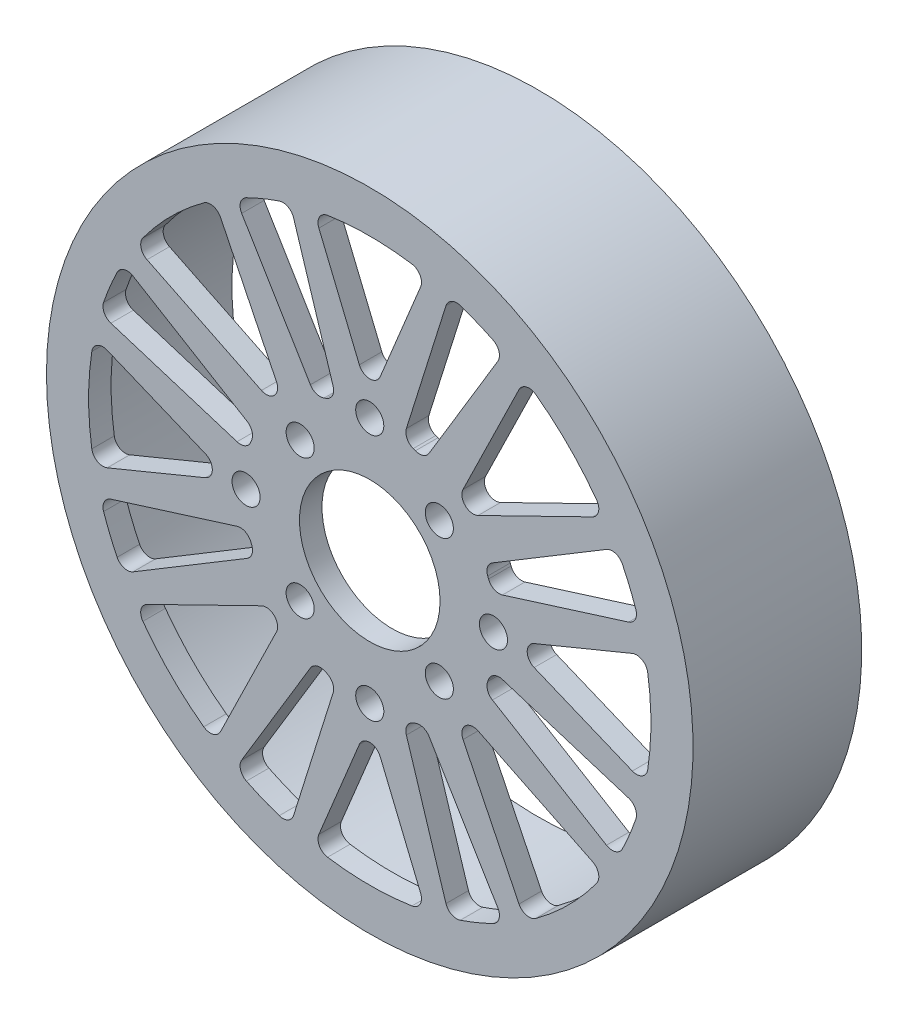
SolidWorks part; units mm, degrees
material "6061 合金"
ref_plane "前视基准面" through (0, 0, 0) normal (0, 0, 1) x (1, 0, 0)
ref_plane "上视基准面" through (0, 0, 0) normal (0, 1, 0) x (1, 0, 0)
ref_plane "右视基准面" through (0, 0, 0) normal (1, 0, 0) x (0, 0, -1)
sketch "草图1" plane through (0, 0, 0) normal (0, 0, 1) x (1, 0, 0)
  circle A0 centre (0, 0) radius 67.5
  dimension "D1" = 135
extrude "凸台-拉伸1" add sketch "草图1" along normal blind 4
sketch "草图2" plane through (0, 0, 4) normal (0, 0, 1) x (1, 0, 0)
  line L0 (0, 17.5) -> (0, 0) construction
  line L1 (0, 0) -> (12.3744, 12.3744) construction
  circle A0 centre (0, 0) radius 22 construction
  circle A1 centre (0, 0) radius 17.5 construction
  circle A2 centre (0, 22) radius 2.5
  circle A3 centre (12.3744, 12.3744) radius 2.5
  dimension "D1" = 35
  dimension "D2" = 44
  dimension "D4" = 5
  dimension "D3" = 45
extrude "切除-拉伸1" cut sketch "草图2" against normal through all
pattern_circular "阵列(圆周)1" count 4 over 360 about axis through (0, 0, 0) along (0, 0, 1) of "切除-拉伸1"
sketch "草图3" plane through (0, 0, 4) normal (0, 0, 1) x (1, 0, 0)
  circle A0 centre (0, 0) radius 12.5
  dimension "D1" = 25
extrude "切除-拉伸2" cut sketch "草图3" against normal through all
sketch "草图4" plane through (0, 0, 0) normal (0, 0, -1) x (-1, 0, 0)
  circle A0 centre (0, 0) radius 67.5
  circle A1 centre (0, 0) radius 54.5
  circle A2 centre (0, 0) radius 67.5 construction
  dimension "D1" = 13
extrude "凸台-拉伸2" add sketch "草图4" along normal offset from surface (26 mm away) 30 up to face at (12.5, 0, 4)
sketch "草图5" plane through (0, 0, -26) normal (0, 0, -1) x (-1, 0, 0)
  circle A0 centre (0, 0) radius 67.5
  circle A1 centre (0, 0) radius 57.5
  dimension "D1" = 10
extrude "切除-拉伸3" cut sketch "草图5" against normal through all
sketch "草图6" plane through (0, 0, 4) normal (0, 0, 1) x (1, 0, 0)
  line L0 (-9.0524, 46.6935) -> (-1.8488, 29.2371)
  line L1 (0, 0) -> (0, 30) construction
  line L2 (9.0524, 46.6935) -> (1.8488, 29.2371)
  line L3 (-13.5532, 46.0406) -> (-6.5123, 23.6064)
  line L4 (13.5532, 46.0406) -> (6.5123, 23.6064)
  line L5 (46.6935, 9.0524) -> (29.2371, 1.8488)
  line L6 (46.6935, -9.0524) -> (29.2371, -1.8488)
  line L7 (46.0406, -13.5532) -> (23.6064, -6.5123)
  line L8 (46.0406, 13.5532) -> (23.6064, 6.5123)
  line L9 (9.0524, -46.6935) -> (1.8488, -29.2371)
  line L10 (-9.0524, -46.6935) -> (-1.8488, -29.2371)
  line L11 (-13.5532, -46.0406) -> (-6.5123, -23.6064)
  line L12 (13.5532, -46.0406) -> (6.5123, -23.6064)
  line L13 (-46.6935, -9.0524) -> (-29.2371, -1.8488)
  line L14 (-46.6935, 9.0524) -> (-29.2371, 1.8488)
  line L15 (-46.0406, 13.5532) -> (-23.6064, 6.5123)
  line L16 (-46.0406, -13.5532) -> (-23.6064, -6.5123)
  line L17 (-16.5882, 19.2636) -> (-26.5456, 39.6181)
  line L18 (0, 0) -> (-12.3744, 12.3744) construction
  line L19 (-19.2636, 16.5882) -> (-39.6181, 26.5456)
  line L20 (-41.7121, 27.5699) -> (-27.5699, 41.7121) construction
  line L21 (-10, 48.9898) -> (10, 48.9898) construction
  line L22 (-22.7777, 42.0989) -> (-10.5577, 21.8157)
  line L23 (-42.0989, 22.7777) -> (-21.8157, 10.5577)
  line L24 (42.0989, 22.7777) -> (21.8157, 10.5577)
  line L25 (19.2636, 16.5882) -> (39.6181, 26.5456)
  line L26 (16.5882, 19.2636) -> (26.5456, 39.6181)
  line L27 (22.7777, 42.0989) -> (10.5577, 21.8157)
  line L28 (22.7777, -42.0989) -> (10.5577, -21.8157)
  line L29 (16.5882, -19.2636) -> (26.5456, -39.6181)
  line L30 (19.2636, -16.5882) -> (39.6181, -26.5456)
  line L31 (42.0989, -22.7777) -> (21.8157, -10.5577)
  line L32 (-42.0989, -22.7777) -> (-21.8157, -10.5577)
  line L33 (-19.2636, -16.5882) -> (-39.6181, -26.5456)
  line L34 (-16.5882, -19.2636) -> (-26.5456, -39.6181)
  line L35 (-22.7777, -42.0989) -> (-10.5577, -21.8157)
  circle A0 centre (0, 0) radius 30 construction
  arc A1 (-29.523, 40.3533) -> (-40.3533, 29.523) centre (0, 0) ccw
  arc A2 (-1.8488, 29.2371) -> (1.8488, 29.2371) centre (0, 30) ccw
  arc A3 (-21.1293, -7.7332) -> (-20.9827, -8.1226) centre (0, 0) ccw
  arc A4 (29.2371, 1.8488) -> (29.2371, -1.8488) centre (30, 0) ccw
  arc A5 (1.8488, -29.2371) -> (-1.8488, -29.2371) centre (0, -30) ccw
  arc A6 (-29.2371, -1.8488) -> (-29.2371, 1.8488) centre (-30, 0) ccw
  arc A7 (-16.5882, 19.2636) -> (-19.2636, 16.5882) centre (-18.3848, 18.3848) cw
  arc A8 (19.2636, 16.5882) -> (16.5882, 19.2636) centre (18.3848, 18.3848) cw
  arc A9 (16.5882, -19.2636) -> (19.2636, -16.5882) centre (18.3848, -18.3848) cw
  arc A10 (-19.2636, -16.5882) -> (-16.5882, -19.2636) centre (-18.3848, -18.3848) cw
  arc A11 (-16.1056, 47.3351) -> (-21.9423, 44.9281) centre (0, 0) ccw
  arc A12 (7.5038, 49.4337) -> (-7.5038, 49.4337) centre (0, 0) ccw
  arc A13 (21.9423, 44.9281) -> (16.1056, 47.3351) centre (0, 0) ccw
  arc A14 (40.3533, 29.523) -> (29.523, 40.3533) centre (0, 0) ccw
  arc A15 (47.3351, 16.1056) -> (44.9281, 21.9423) centre (0, 0) ccw
  arc A16 (49.4337, -7.5038) -> (49.4337, 7.5038) centre (0, 0) ccw
  arc A17 (44.9281, -21.9423) -> (47.3351, -16.1056) centre (0, 0) ccw
  arc A18 (29.523, -40.3533) -> (40.3533, -29.523) centre (0, 0) ccw
  arc A19 (16.1056, -47.3351) -> (21.9423, -44.9281) centre (0, 0) ccw
  arc A20 (-7.5038, -49.4337) -> (7.5038, -49.4337) centre (0, 0) ccw
  arc A21 (-21.9423, -44.9281) -> (-16.1056, -47.3351) centre (0, 0) ccw
  arc A22 (-40.3533, -29.523) -> (-29.523, -40.3533) centre (0, 0) ccw
  arc A23 (-47.3351, -16.1056) -> (-44.9281, -21.9423) centre (0, 0) ccw
  arc A24 (-44.9281, 21.9423) -> (-47.3351, 16.1056) centre (0, 0) ccw
  arc A25 (-49.4337, 7.5038) -> (-49.4337, -7.5038) centre (0, 0) ccw
  arc A26 (-8.1226, -20.9827) -> (-7.7332, -21.1293) centre (0, 0) ccw
  arc A27 (-20.9827, 8.1226) -> (-21.1293, 7.7332) centre (0, 0) ccw
  arc A28 (-7.7332, 21.1293) -> (-8.1226, 20.9827) centre (0, 0) ccw
  arc A29 (8.1226, 20.9827) -> (7.7332, 21.1293) centre (0, 0) ccw
  arc A30 (21.1293, 7.7332) -> (20.9827, 8.1226) centre (0, 0) ccw
  arc A31 (20.9827, -8.1226) -> (21.1293, -7.7332) centre (0, 0) ccw
  arc A32 (7.7332, -21.1293) -> (8.1226, -20.9827) centre (0, 0) ccw
  arc A33 (6.5123, 23.6064) -> (7.7332, 21.1293) centre (8.4206, 23.0075) ccw
  arc A34 (10.5577, 21.8157) -> (8.1226, 20.9827) centre (8.8446, 22.8478) cw
  arc A35 (21.8157, 10.5577) -> (20.9827, 8.1226) centre (22.8478, 8.8446) ccw
  arc A36 (23.6064, 6.5123) -> (21.1293, 7.7332) centre (23.0075, 8.4206) cw
  arc A37 (23.6064, -6.5123) -> (21.1293, -7.7332) centre (23.0075, -8.4206) ccw
  arc A38 (21.8157, -10.5577) -> (20.9827, -8.1226) centre (22.8478, -8.8446) cw
  arc A39 (10.5577, -21.8157) -> (8.1226, -20.9827) centre (8.8446, -22.8478) ccw
  arc A40 (6.5123, -23.6064) -> (7.7332, -21.1293) centre (8.4206, -23.0075) cw
  arc A41 (-6.5123, -23.6064) -> (-7.7332, -21.1293) centre (-8.4206, -23.0075) ccw
  arc A42 (-10.5577, -21.8157) -> (-8.1226, -20.9827) centre (-8.8446, -22.8478) cw
  arc A43 (-21.8157, -10.5577) -> (-20.9827, -8.1226) centre (-22.8478, -8.8446) ccw
  arc A44 (-23.6064, -6.5123) -> (-21.1293, -7.7332) centre (-23.0075, -8.4206) cw
  arc A45 (-23.6064, 6.5123) -> (-21.1293, 7.7332) centre (-23.0075, 8.4206) ccw
  arc A46 (-21.8157, 10.5577) -> (-20.9827, 8.1226) centre (-22.8478, 8.8446) cw
  arc A47 (-42.0989, 22.7777) -> (-44.9281, 21.9423) centre (-43.131, 21.0646) ccw
  arc A48 (-46.0406, 13.5532) -> (-47.3351, 16.1056) centre (-45.4417, 15.4614) cw
  arc A49 (-46.6935, 9.0524) -> (-49.4337, 7.5038) centre (-47.4564, 7.2036) ccw
  arc A50 (-46.6935, -9.0524) -> (-49.4337, -7.5038) centre (-47.4564, -7.2036) cw
  arc A51 (-46.0406, -13.5532) -> (-47.3351, -16.1056) centre (-45.4417, -15.4614) ccw
  arc A52 (-42.0989, -22.7777) -> (-44.9281, -21.9423) centre (-43.131, -21.0646) cw
  arc A53 (-39.6181, -26.5456) -> (-40.3533, -29.523) centre (-38.7392, -28.3421) ccw
  arc A54 (-26.5456, -39.6181) -> (-29.523, -40.3533) centre (-28.3421, -38.7392) cw
  arc A55 (-22.7777, -42.0989) -> (-21.9423, -44.9281) centre (-21.0646, -43.131) ccw
  arc A56 (-13.5532, -46.0406) -> (-16.1056, -47.3351) centre (-15.4614, -45.4417) cw
  arc A57 (-9.0524, -46.6935) -> (-7.5038, -49.4337) centre (-7.2036, -47.4564) ccw
  arc A58 (9.0524, -46.6935) -> (7.5038, -49.4337) centre (7.2036, -47.4564) cw
  arc A59 (13.5532, -46.0406) -> (16.1056, -47.3351) centre (15.4614, -45.4417) ccw
  arc A60 (22.7777, -42.0989) -> (21.9423, -44.9281) centre (21.0646, -43.131) cw
  arc A61 (26.5456, -39.6181) -> (29.523, -40.3533) centre (28.3421, -38.7392) ccw
  arc A62 (39.6181, -26.5456) -> (40.3533, -29.523) centre (38.7392, -28.3421) cw
  arc A63 (42.0989, -22.7777) -> (44.9281, -21.9423) centre (43.131, -21.0646) ccw
  arc A64 (46.0406, -13.5532) -> (47.3351, -16.1056) centre (45.4417, -15.4614) cw
  arc A65 (46.6935, -9.0524) -> (49.4337, -7.5038) centre (47.4564, -7.2036) ccw
  arc A66 (46.6935, 9.0524) -> (49.4337, 7.5038) centre (47.4564, 7.2036) cw
  arc A67 (46.0406, 13.5532) -> (47.3351, 16.1056) centre (45.4417, 15.4614) ccw
  arc A68 (42.0989, 22.7777) -> (44.9281, 21.9423) centre (43.131, 21.0646) cw
  arc A69 (39.6181, 26.5456) -> (40.3533, 29.523) centre (38.7392, 28.3421) ccw
  arc A70 (26.5456, 39.6181) -> (29.523, 40.3533) centre (28.3421, 38.7392) cw
  arc A71 (22.7777, 42.0989) -> (21.9423, 44.9281) centre (21.0646, 43.131) ccw
  arc A72 (13.5532, 46.0406) -> (16.1056, 47.3351) centre (15.4614, 45.4417) cw
  arc A73 (9.0524, 46.6935) -> (7.5038, 49.4337) centre (7.2036, 47.4564) ccw
  arc A74 (-9.0524, 46.6935) -> (-7.5038, 49.4337) centre (-7.2036, 47.4564) cw
  arc A75 (-39.6181, 26.5456) -> (-40.3533, 29.523) centre (-38.7392, 28.3421) cw
  arc A76 (-26.5456, 39.6181) -> (-29.523, 40.3533) centre (-28.3421, 38.7392) ccw
  arc A77 (-13.5532, 46.0406) -> (-16.1056, 47.3351) centre (-15.4614, 45.4417) ccw
  arc A78 (-22.7777, 42.0989) -> (-21.9423, 44.9281) centre (-21.0646, 43.131) cw
  arc A79 (-10.5577, 21.8157) -> (-8.1226, 20.9827) centre (-8.8446, 22.8478) ccw
  arc A80 (-6.5123, 23.6064) -> (-7.7332, 21.1293) centre (-8.4206, 23.0075) cw
  circle A81 centre (0, 0) radius 26 construction
  point P83 (5.9166, 21.7082)
  point P86 (9.6577, 20.3219)
  point P89 (20.3219, 9.6577)
  point P112 (-20.3219, 9.6577)
  point P115 (-43.9288, 23.8802)
  point P166 (14.154, 47.9548)
  point P181 (-14.154, 47.9548)
  point P184 (-23.8802, 43.9288)
  point P187 (-9.6577, 20.3219)
  point P190 (-5.9166, 21.7082)
  dimension "D1" = 2
  dimension "D3" = 20
  dimension "D4" = 45
  dimension "D5" = 2
  dimension "D11" = 50
  dimension "D12" = 2
  dimension "D13" = 8.5
  dimension "D2" = 30
  dimension "D6" = 26
  dimension "D8" = 5
  dimension "D9" = 5
  dimension "D14" = 8.5
  dimension "D7" = 4
  dimension "D10" = 4
extrude "切除-拉伸4" cut sketch "草图6" against normal through all
